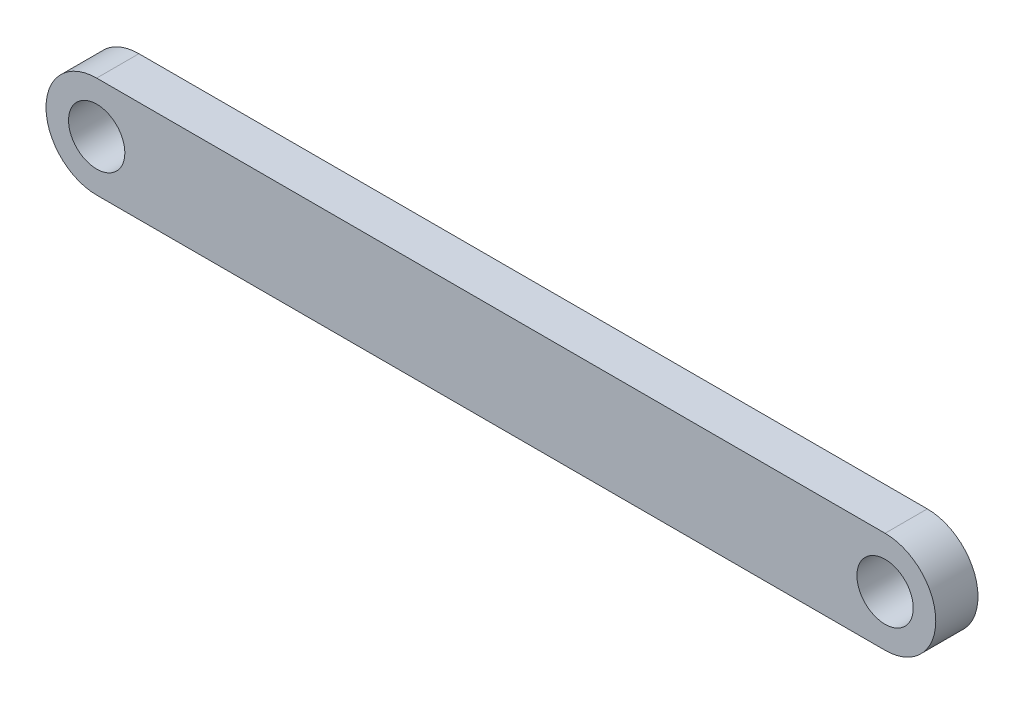
SolidWorks part; units mm, degrees
ref_plane "Plan de face" through (0, 0, 0) normal (0, 0, 1) x (1, 0, 0)
ref_plane "Plan de dessus" through (0, 0, 0) normal (0, 1, 0) x (1, 0, 0)
ref_plane "Plan de droite" through (0, 0, 0) normal (1, 0, 0) x (0, 0, -1)
sketch "Esquisse1" plane through (0, 0, 0) normal (0, 0, 1) x (1, 0, 0)
  line L0 (-71.1744, 0) -> (208.8256, 0) construction
  line L1 (-71.1744, 18) -> (208.8256, 18)
  line L2 (-71.1744, -18) -> (208.8256, -18)
  circle A0 centre (-71.1744, 0) radius 10
  circle A1 centre (208.8256, 0) radius 10
  arc A2 (-71.1744, -18) -> (-71.1744, 18) centre (-71.1744, 0) cw
  arc A3 (208.8256, 18) -> (208.8256, -18) centre (208.8256, 0) cw
  dimension "D1" = 20
  dimension "D2" = 20
  dimension "D3" = 280
  dimension "D5" = 0
  dimension "D6" = 0
  dimension "D4" = 18
extrude "Boss.-Extru.1" add sketch "Esquisse1" along normal blind 15
